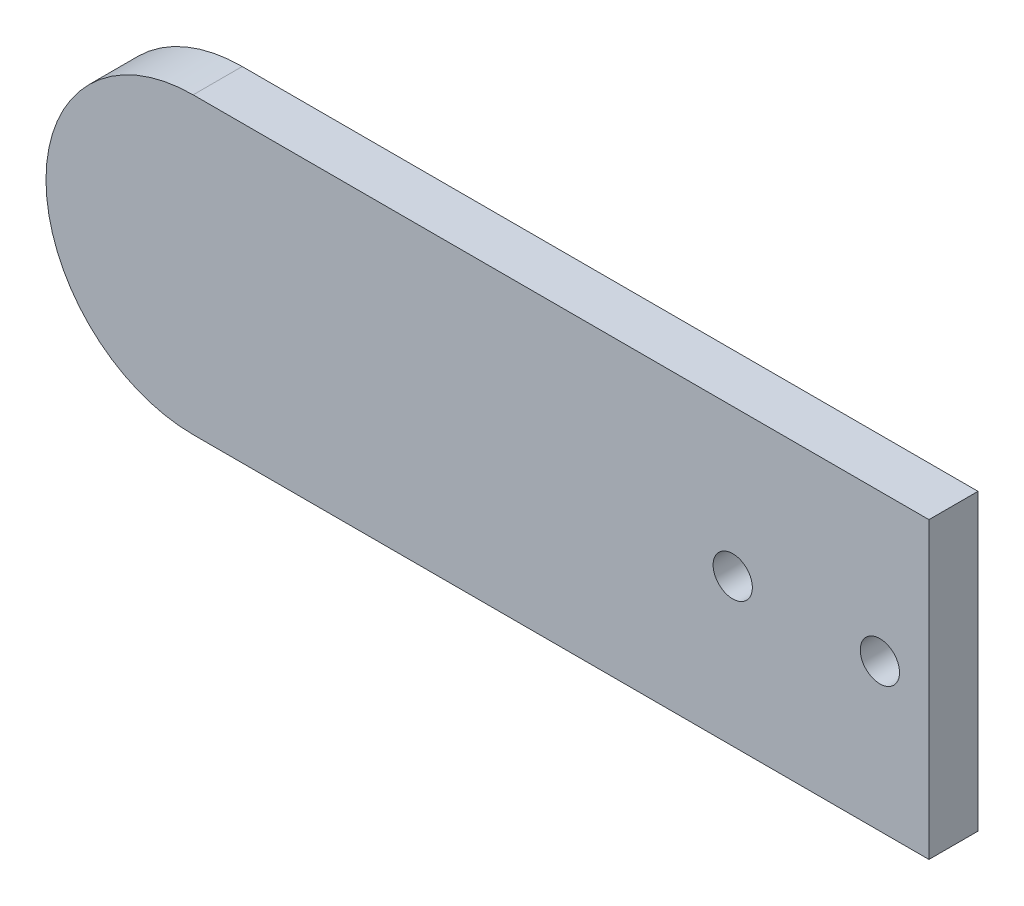
SolidWorks part; units mm, degrees
ref_plane "Front Plane" through (0, 0, 0) normal (0, 0, 1) x (1, 0, 0)
ref_plane "Top Plane" through (0, 0, 0) normal (0, 1, 0) x (1, 0, 0)
ref_plane "Right Plane" through (0, 0, 0) normal (1, 0, 0) x (0, 0, -1)
sketch "Sketch1" plane through (0, 0, 0) normal (0, 0, 1) x (1, 0, 0)
  line L1 (-30, 15) -> (45, 15)
  line L3 (-30, -15) -> (45, -15)
  line L4 (45, 15) -> (45, -15)
  line L5 (0, 0) -> (45, -15) construction
  line L6 (0, 0) -> (45, 15) construction
  arc A0 (-30, 15) -> (-30, -15) centre (-30, 0) ccw
  point P0 (0, 0)
extrude "Boss-Extrude2" add sketch "Sketch1" along normal blind 5
sketch "Sketch3" plane through (0, 0, 0) normal (0, 0, -1) x (-1, 0, 0)
  line L0 (-45, -15) -> (-45, 15) construction
  line L1 (-45, 15) -> (30, 15) construction
  circle A0 centre (-40, 0) radius 2
  circle A1 centre (-25, 0) radius 2
  dimension "D1" = 4
  dimension "D2" = 4
  dimension "D3" = 5
  dimension "D4" = 20
  dimension "D5" = 15
  dimension "D6" = 15
extrude "Cut-Extrude1" cut sketch "Sketch3" against normal through all
sketch "Sketch4" plane through (0, 0, 0) normal (0, 0, -1) x (-1, 0, 0)
  line L0 (-45, -15) -> (-45, 15) construction
  circle A0 centre (20, 0) radius 7.5
  dimension "D1" = 15
  dimension "D2" = 65
extrude "Boss-Extrude5" add sketch "Sketch4" along normal blind 1
sketch "Sketch6" plane through (0, 0, -1) normal (0, 0, -1) x (-1, 0, 0)
  circle A0 centre (20, 0) radius 5
  dimension "D1" = 10
extrude "Boss-Extrude6" add sketch "Sketch6" along normal blind 5
